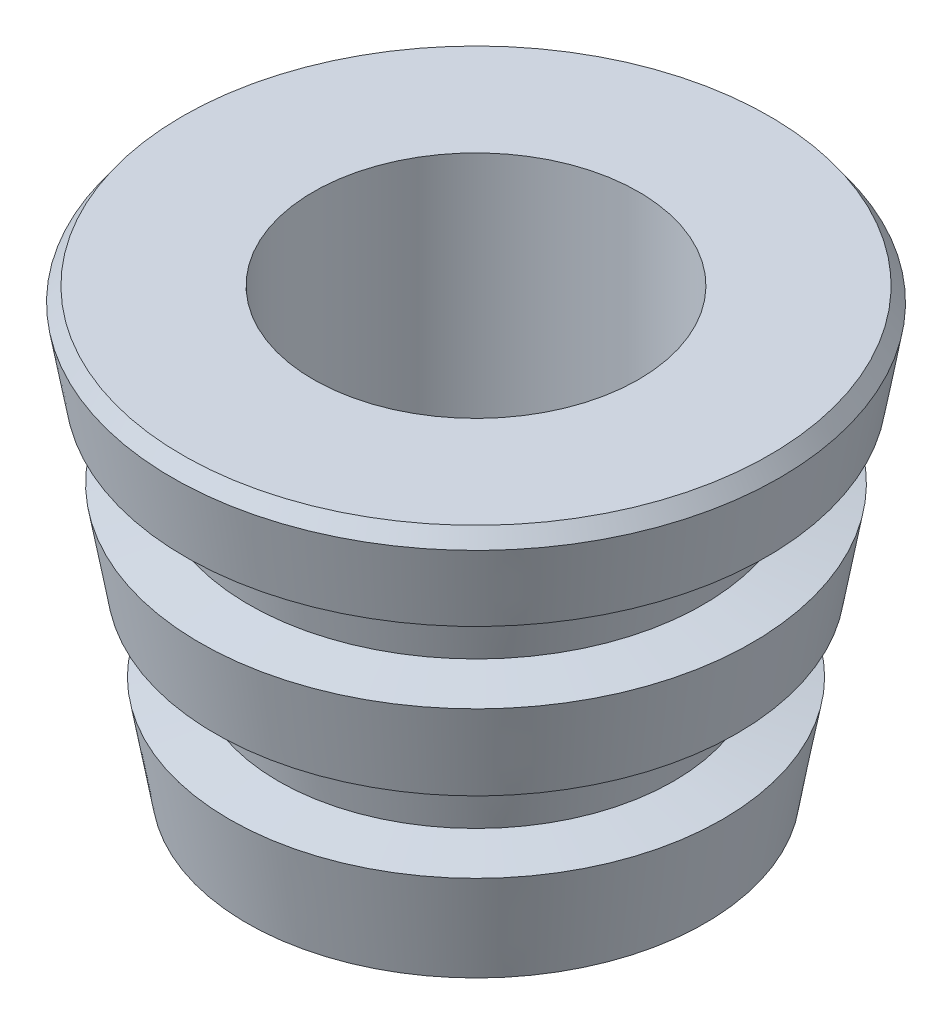
SolidWorks part; units mm, degrees
ref_plane "Piano frontale" through (0, 0, 0) normal (0, 0, 1) x (1, 0, 0)
ref_plane "Piano superiore" through (0, 0, 0) normal (0, 1, 0) x (1, 0, 0)
ref_plane "Piano destro" through (0, 0, 0) normal (1, 0, 0) x (0, 0, -1)
sketch "Schizzo1" plane through (0, 0, 0) normal (0, 0, 1) x (1, 0, 0)
  line L0 (0, 0) -> (0, -14.8) construction
  line L1 (0, -14.8) -> (-7.75, -14.8)
  line L2 (-7.75, -14.8) -> (-10.3596, 0)
  line L3 (-10.3596, 0) -> (0, 0)
  line L4 (0, 0) -> (0, -14.8)
  dimension "D1" = 14.8
  dimension "D2" = 10
  dimension "D3" = 7.75
revolve "Rivoluzione1" add sketch "Schizzo1" angle 360 about L0
sketch "Schizzo2" plane through (0, 0, 0) normal (0, 0, 1) x (1, 0, 0)
  line L0 (0, 0) -> (0, -14.8) construction
  line L1 (10.3596, 0) -> (-10.3596, 0) construction
  line L2 (-7.75, -14.8) -> (7.75, -14.8) construction
  line L3 (-9.8241, -3.0369) -> (-8.1697, -2.7452)
  line L4 (-9.8241, -3.0369) -> (-9.3379, -5.7944)
  line L5 (-8.1697, -2.7452) -> (-7.6835, -5.5027)
  line L6 (-9.3379, -5.7944) -> (-7.6835, -5.5027)
  line L7 (-10.3596, 0) -> (-7.75, -14.8) construction
  line L8 (-8.1697, -2.7452) -> (-8.0076, -3.6644) construction
  line L9 (-8.0076, -3.6644) -> (-7.8455, -4.5835) construction
  line L10 (-7.8455, -4.5835) -> (-7.6835, -5.5027) construction
  line L11 (-8.8241, -8.7082) -> (-8.3379, -11.4657)
  line L12 (-7.8455, -4.5835) -> (-9.5, -4.8753) construction
  line L13 (-9.5, -4.8753) -> (0, -4.8753) construction
  line L14 (-8.8241, -8.7082) -> (-7.1697, -8.4165)
  line L15 (-8.3379, -11.4657) -> (-6.6835, -11.174)
  line L16 (-7.1697, -8.4165) -> (-6.6835, -11.174)
  line L17 (-6.6835, -11.174) -> (-6.8455, -10.2548) construction
  line L18 (-6.8455, -10.2548) -> (-8.5, -10.5465) construction
  line L19 (-8.5, -10.5465) -> (0, -10.5465) construction
  dimension "D1" = 1.68
  dimension "D2" = 2.8
  dimension "D3" = 9.5
  dimension "D4" = 1.68
  dimension "D5" = 2.8
  dimension "D6" = 8.5
revolve "Taglia-Rivoluzione1" cut sketch "Schizzo2" angle 360 about L0
sketch "Schizzo5" plane through (0, -14.8, 0) normal (0, -1, 0) x (1, 0, 0)
  circle A1 centre (0, 0) radius 7.75
  circle A2 centre (0, 0) radius 7.75
  dimension "D1" = 0
chamfer "Smusso2" distance 0.5 angle 45 1 edges at (-10.3596, 0, 0)
sketch "Schizzo6" plane through (0, -14.8, 0) normal (0, -1, 0) x (1, 0, 0)
  circle A0 centre (0, 0) radius 5.5
  dimension "D1" = 11
extrude "Taglio-Estrusione1" cut sketch "Schizzo6" against normal through all
